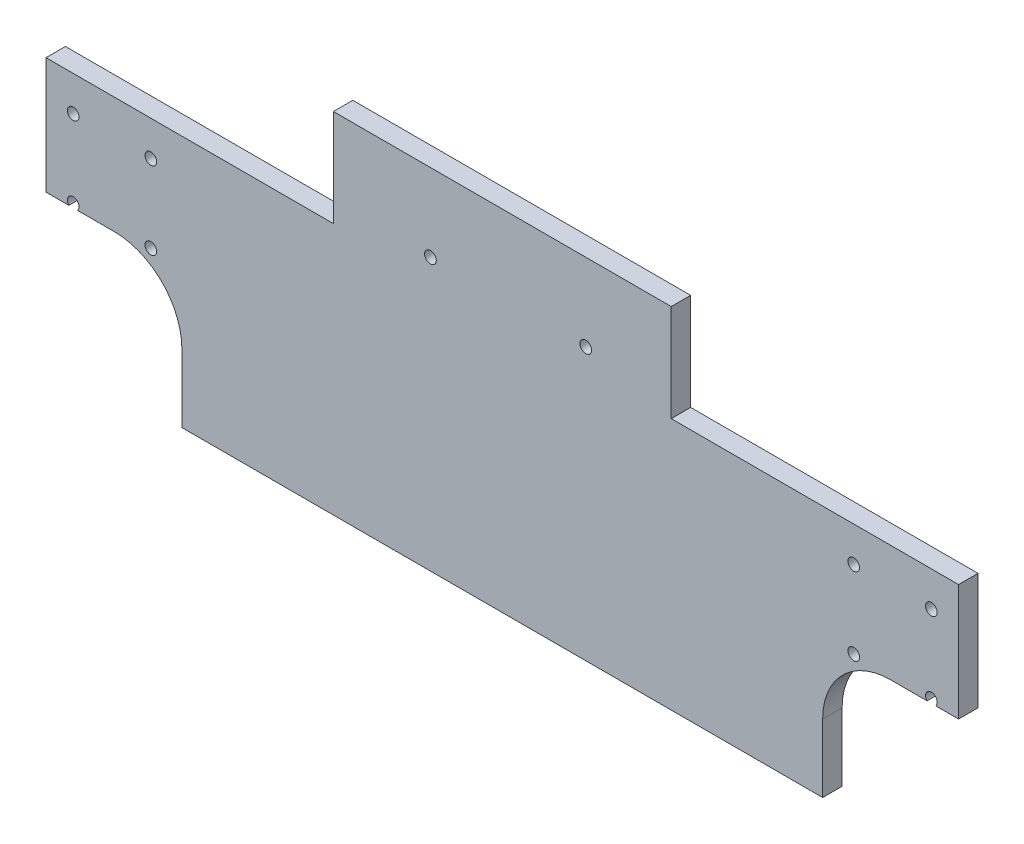
SolidWorks part; units mm, degrees
ref_plane "Plan de face" through (0, 0, 0) normal (0, 0, 1) x (1, 0, 0)
ref_plane "Plan de dessus" through (0, 0, 0) normal (0, 1, 0) x (1, 0, 0)
ref_plane "Plan de droite" through (0, 0, 0) normal (1, 0, 0) x (0, 0, -1)
sketch "Esquisse1" plane through (0, 0, 0) normal (0, 0, 1) x (1, 0, 0)
  line L0 (0, 0) -> (235, 0)
  line L1 (235, 0) -> (235, 65)
  line L2 (235, 65) -> (161, 65)
  line L3 (161, 65) -> (161, 90)
  line L4 (161, 90) -> (74, 90)
  line L5 (74, 90) -> (74, 65)
  line L6 (74, 65) -> (0, 65)
  line L7 (0, 65) -> (0, 0)
  line L8 (17.5, 35) -> (0, 35)
  line L9 (35, 17.5) -> (35, 0)
  line L10 (200, 17.5) -> (200, 0)
  line L11 (235, 35) -> (217.5, 35)
  circle A0 centre (17.5, 17.5) radius 17.5
  circle A1 centre (217.5, 17.5) radius 17.5
  circle A2 centre (7, 56) radius 1.5
  circle A3 centre (7, 36) radius 1.5
  circle A4 centre (27, 56) radius 1.5
  circle A5 centre (27, 36) radius 1.5
  circle A6 centre (208, 56) radius 1.5
  circle A7 centre (228, 56) radius 1.5
  circle A8 centre (208, 36) radius 1.5
  circle A9 centre (228, 36) radius 1.5
  circle A10 centre (99, 70) radius 1.5
  circle A11 centre (139, 70) radius 1.5
  dimension "D7" = 35
  dimension "D8" = 35
  dimension "D13" = 3
  dimension "D14" = 3
  dimension "D15" = 3
  dimension "D16" = 3
  dimension "D21" = 3
  dimension "D22" = 3
  dimension "D23" = 3
  dimension "D24" = 3
  dimension "D37" = 3
  dimension "D38" = 3
  dimension "D1" = 87
  dimension "D2" = 74
  dimension "D3" = 74
  dimension "D4" = 65
  dimension "D5" = 65
  dimension "D6" = 25
  dimension "D9" = 17.5
  dimension "D10" = 17.5
  dimension "D11" = 17.5
  dimension "D12" = 17.5
  dimension "D17" = 7
  dimension "D18" = 7
  dimension "D19" = 20
  dimension "D20" = 20
  dimension "D25" = 20
  dimension "D26" = 20
  dimension "D27" = 7
  dimension "D28" = 7
  dimension "D29" = 20
  dimension "D30" = 20
  dimension "D31" = 20
  dimension "D32" = 20
  dimension "D33" = 36
  dimension "D34" = 36
  dimension "D35" = 36
  dimension "D36" = 36
  dimension "D39" = 25
  dimension "D40" = 65
  dimension "D41" = 5
  dimension "D42" = 5
extrude "Boss.-Extru.1" add sketch "Esquisse1" along normal blind 5 contours A9 L11 L1 L2 L3 L4 L5 L6 L7 L8 A3 A0 L9 L0 L10 A1 A11 A10 A8 A7 A6 A5 A4 A2
